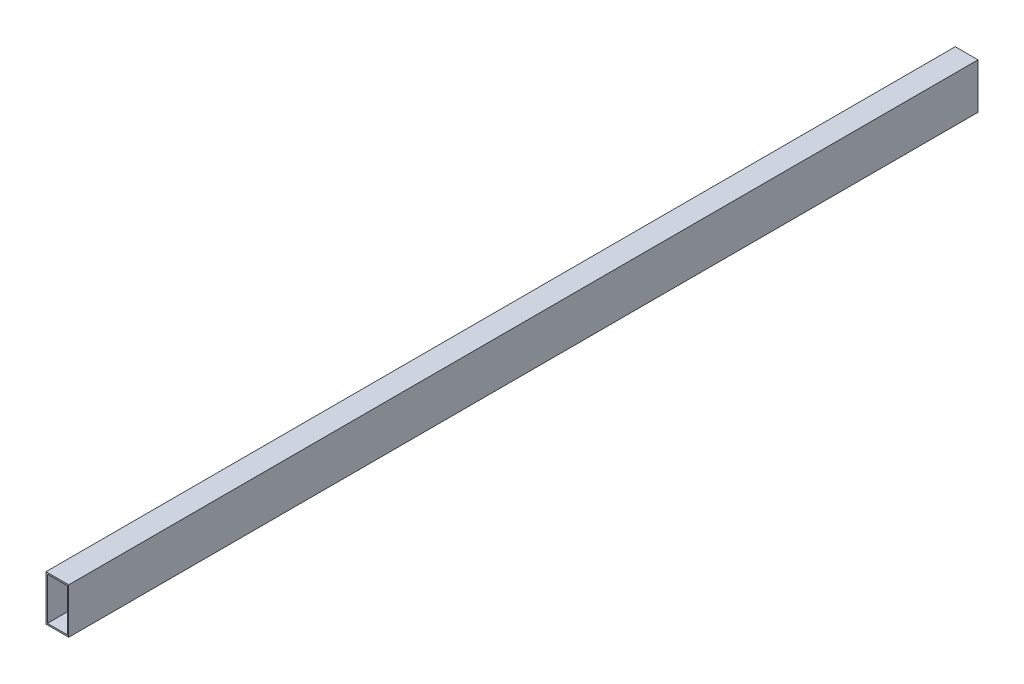
SolidWorks part; units mm, degrees
ref_plane "Front Plane" through (0, 0, 0) normal (0, 0, 1) x (1, 0, 0)
ref_plane "Top Plane" through (0, 0, 0) normal (0, 1, 0) x (1, 0, 0)
ref_plane "Right Plane" through (0, 0, 0) normal (1, 0, 0) x (0, 0, -1)
sketch "Sketch1" plane through (0, 0, 0) normal (0, 0, 1) x (1, 0, 0)
  line L0 (0, 0) -> (25.4, 50.8) construction
  line L1 (0, 0) -> (25.4, 0)
  line L2 (0, 0) -> (0, 50.8)
  line L3 (0, 50.8) -> (25.4, 50.8)
  line L4 (25.4, 0) -> (25.4, 50.8)
  line L6 (1.5875, 49.2125) -> (23.8125, 49.2125)
  line L7 (1.5875, 49.2125) -> (1.5875, 1.5875)
  line L8 (1.5875, 1.5875) -> (23.8125, 1.5875)
  line L9 (23.8125, 49.2125) -> (23.8125, 1.5875)
  line L10 (1.5875, 49.2125) -> (23.8125, 1.5875) construction
  line L11 (1.5875, 1.5875) -> (23.8125, 49.2125) construction
  point P5 (12.7, 25.4)
  point P6 (12.7, 25.4)
  dimension "D1" = 25.4
  dimension "D2" = 50.8
  dimension "D3" = 1.5875
  dimension "D4" = 1.5875
extrude "Boss-Extrude1" add sketch "Sketch1" along normal blind 1016
ref_plane "Plane1" through (0, 25.4, 0) normal (0, -1, 0) x (-1, 0, 0)
ref_plane "Plane2" through (12.7, 0, 0) normal (1, 0, 0) x (0, 0, -1)
